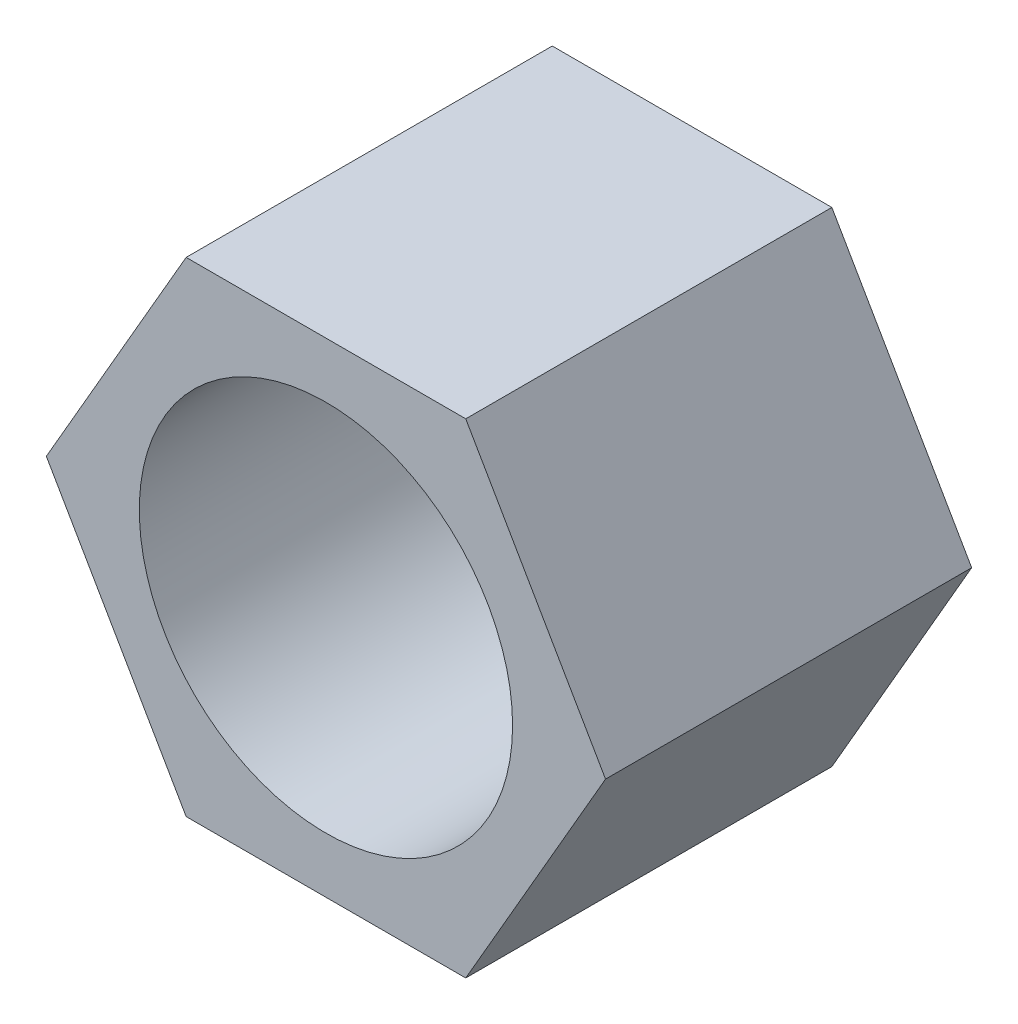
SolidWorks part; units mm, degrees
ref_plane "Front Plane" through (0, 0, 0) normal (0, 0, 1) x (1, 0, 0)
ref_plane "Top Plane" through (0, 0, 0) normal (0, 1, 0) x (1, 0, 0)
ref_plane "Right Plane" through (0, 0, 0) normal (1, 0, 0) x (0, 0, -1)
sketch "Sketch1" plane through (0, 0, 0) normal (0, 0, 1) x (1, 0, 0)
  line L1 (10.9985, 0) -> (5.4993, 9.525)
  line L2 (5.4993, 9.525) -> (-5.4993, 9.525)
  line L3 (-5.4993, 9.525) -> (-10.9985, 0)
  line L4 (-10.9985, 0) -> (-5.4993, -9.525)
  line L5 (-5.4993, -9.525) -> (5.4993, -9.525)
  line L6 (5.4993, -9.525) -> (10.9985, 0)
  circle A0 centre (0, 0) radius 9.525 construction
  dimension "D1" = 19.05
extrude "Boss-Extrude1" add sketch "Sketch1" along normal mid plane 14.4018
sketch "Sketch11" plane through (0, 0, 7.2009) normal (0, 0, 1) x (1, 0, 0)
  circle A0 centre (0, 0) radius 7.3419
  dimension "D1" = 14.6837
sketch "Sketch12" plane through (0, 0, -7.2009) normal (0, 0, -1) x (-1, 0, 0)
  circle A0 centre (0, 0) radius 3.5719
  dimension "D1" = 7.1437
extrude "Cut-Extrude2" cut sketch "Sketch12" against normal blind 3.175
extrude "Cut-Extrude3" cut sketch "Sketch11" against normal blind 11.2268
cosmetic thread "Cosmetic Thread1" parameters "D1"=5, "D2"=15.875
cosmetic thread "Cosmetic Thread2" parameters "D1"=5, "D2"=15.875
